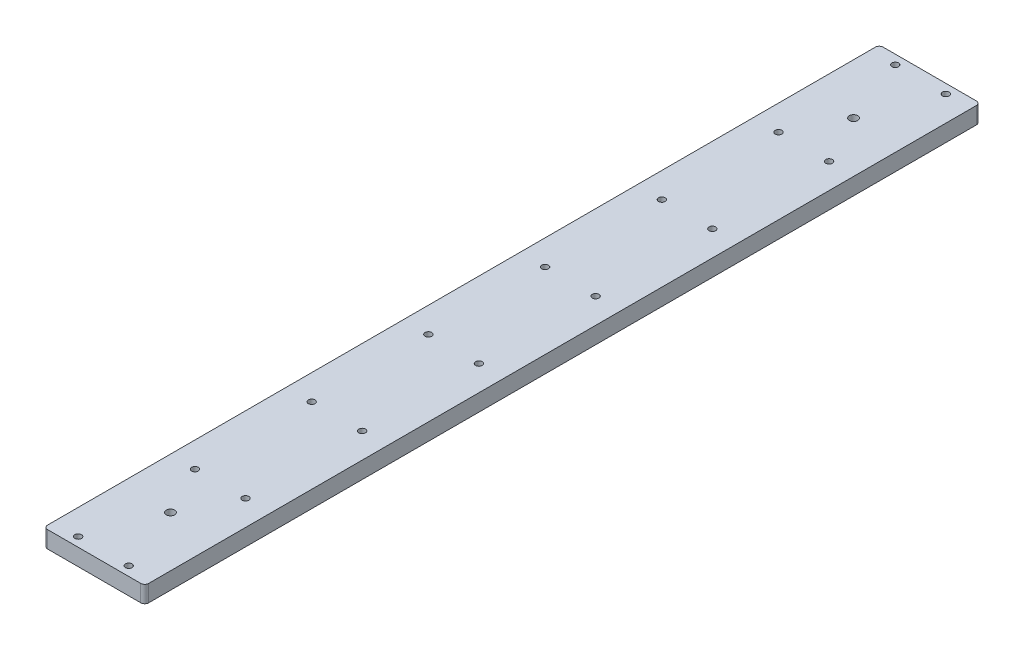
SolidWorks part; units mm, degrees
ref_plane "Front Plane" through (0, 0, 0) normal (0, 0, 1) x (1, 0, 0)
ref_plane "Top Plane" through (0, 0, 0) normal (0, 1, 0) x (1, 0, 0)
ref_plane "Right Plane" through (0, 0, 0) normal (1, 0, 0) x (0, 0, -1)
sketch "Sketch1" plane through (0, 0, 0) normal (0, 0, 1) x (1, 0, 0)
  line L1 (38.1, -6.35) -> (-38.1, -6.35)
  line L2 (38.1, -6.35) -> (38.1, 6.35)
  line L3 (38.1, 6.35) -> (-38.1, 6.35)
  line L4 (-38.1, -6.35) -> (-38.1, 6.35)
  line L5 (0, 6.35) -> (0, -6.35) construction
  line L6 (38.1, 0) -> (-38.1, 0) construction
  point P0 (0, 0)
  dimension "D1" = 12.7
  dimension "D2" = 76.2
extrude "Boss-Extrude1" add sketch "Sketch1" along normal blind 630
sketch "Sketch2" plane through (0, -6.35, 0) normal (0, -1, 0) x (1, 0, 0)
  circle A2 centre (0, 57.5) radius 3.175
  circle A3 centre (0, 572.5) radius 3.175
extrude "Cut-Extrude1" cut sketch "Sketch2" against normal through all
sketch "Sketch3" plane through (0, -6.35, 0) normal (0, -1, 0) x (1, 0, 0)
  circle A16 centre (19.05, 7) radius 2.5
  circle A17 centre (-19.05, 7) radius 2.5
  circle A18 centre (-19.05, 95) radius 2.5
  circle A19 centre (-19.05, 183) radius 2.5
  circle A20 centre (-19.05, 271) radius 2.5
  circle A21 centre (-19.05, 359) radius 2.5
  circle A22 centre (-19.05, 447) radius 2.5
  circle A23 centre (-19.05, 535) radius 2.5
  circle A24 centre (-19.05, 623) radius 2.5
  circle A25 centre (19.05, 95) radius 2.5
  circle A26 centre (19.05, 183) radius 2.5
  circle A27 centre (19.05, 271) radius 2.5
  circle A28 centre (19.05, 359) radius 2.5
  circle A29 centre (19.05, 447) radius 2.5
  circle A30 centre (19.05, 535) radius 2.5
  circle A31 centre (19.05, 623) radius 2.5
  dimension "D1" = 8
extrude "Cut-Extrude2" cut sketch "Sketch3" against normal through all
fillet "Fillet1" radius 3 4 edges at (38.1, 0, 0) (-38.1, 0, 0) (-38.1, 0, 630) (38.1, 0, 630)
